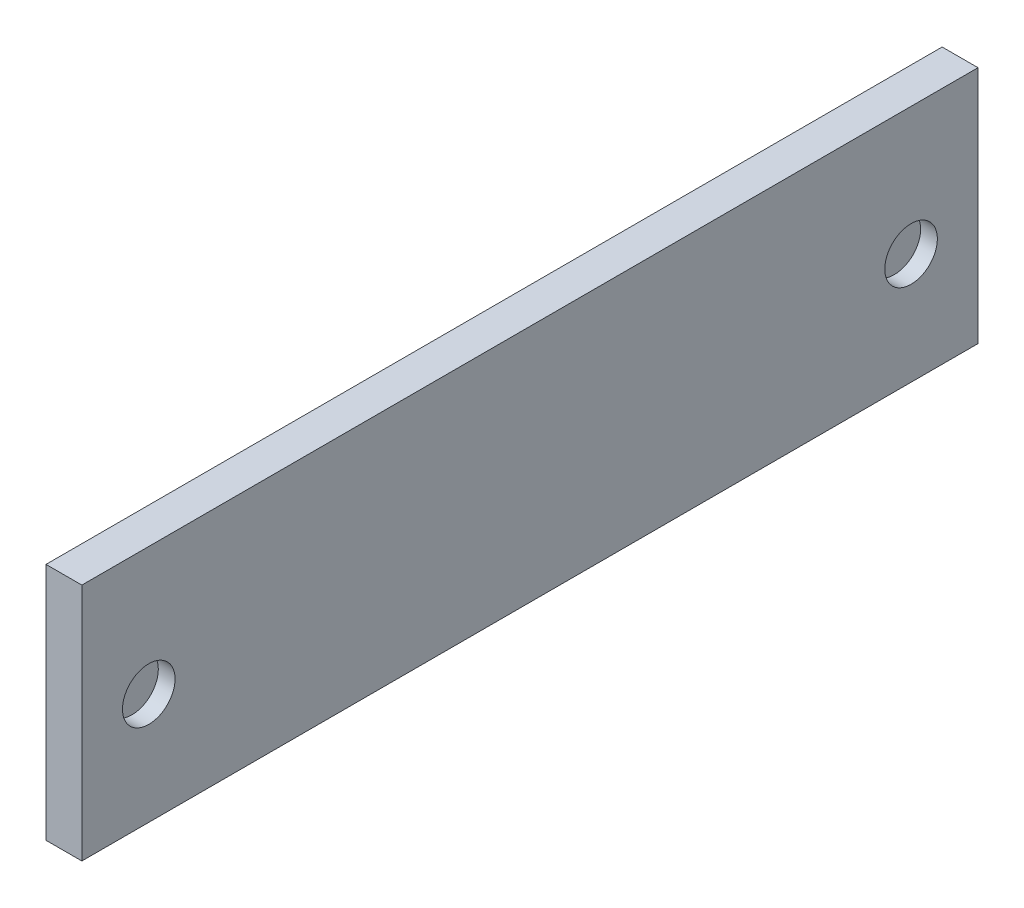
SolidWorks part; units mm, degrees
ref_plane "Alzado" through (0, 0, 0) normal (0, 0, 1) x (1, 0, 0)
ref_plane "Planta" through (0, 0, 0) normal (0, 1, 0) x (1, 0, 0)
ref_plane "Vista lateral" through (0, 0, 0) normal (1, 0, 0) x (0, 0, -1)
sketch "Croquis1" plane through (0, 0, 0) normal (1, 0, 0) x (0, 0, -1)
  line L1 (0, 0) -> (375, 0)
  line L2 (0, 0) -> (0, 100)
  line L3 (0, 100) -> (375, 100)
  line L4 (375, 0) -> (375, 100)
  dimension "D1" = 375
  dimension "D2" = 100
extrude "Saliente-Extruir1" add sketch "Croquis1" along normal blind 15
sketch "Croquis2" plane through (15, 0, 0) normal (1, 0, 0) x (0, 0, -1)
  line L0 (0, 0) -> (375, 0) construction
  line L1 (28, 46.5) -> (0, 46.5) construction
  line L2 (0, 100) -> (0, 0) construction
  line L3 (347, 46.5) -> (375, 46.5) construction
  line L4 (375, 0) -> (375, 100) construction
  circle A0 centre (28, 46.5) radius 11
  circle A1 centre (347, 46.5) radius 11
  dimension "D1" = 22
  dimension "D2" = 46.5
  dimension "D3" = 28
extrude "Cortar-Extruir1" cut sketch "Croquis2" against normal blind 7
